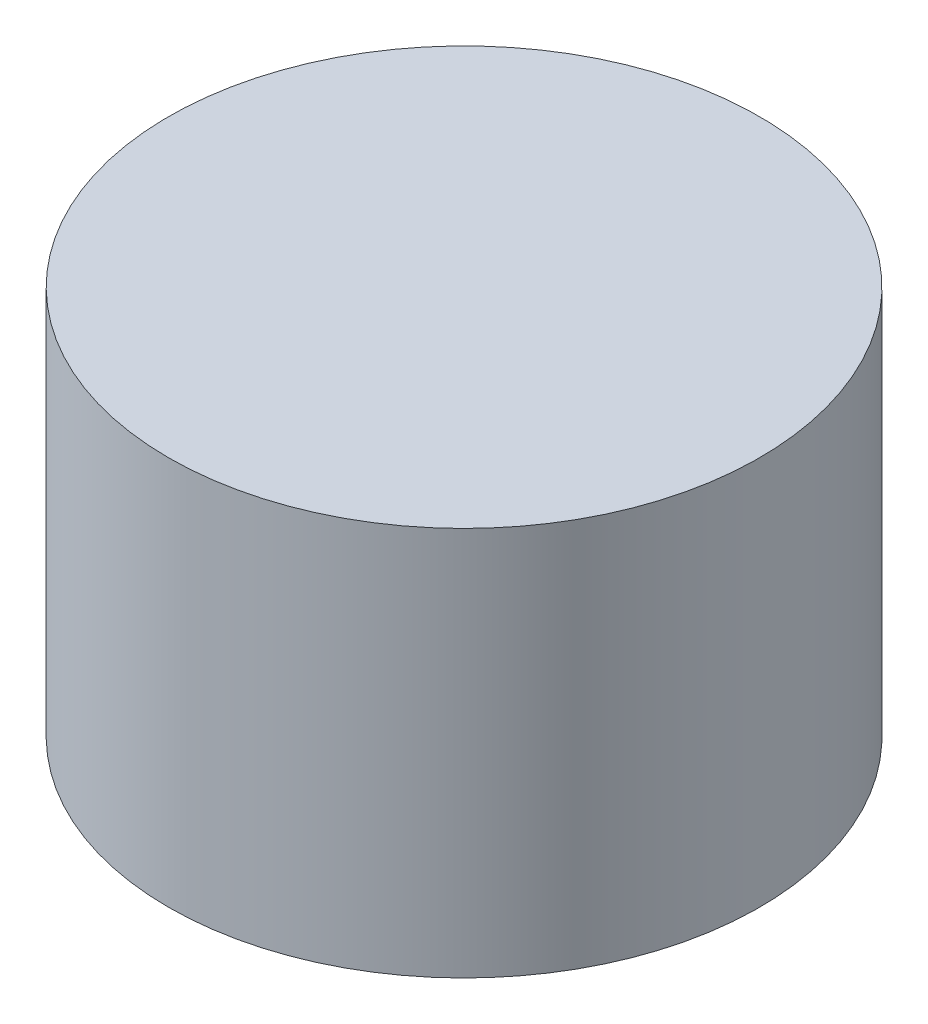
SolidWorks part; units mm, degrees
ref_plane "Front Plane" through (0, 0, 0) normal (0, 0, 1) x (1, 0, 0)
ref_plane "Top Plane" through (0, 0, 0) normal (0, 1, 0) x (1, 0, 0)
ref_plane "Right Plane" through (0, 0, 0) normal (1, 0, 0) x (0, 0, -1)
sketch "Sketch1" plane through (0, 0, 0) normal (0, 1, 0) x (1, 0, 0)
  circle A0 centre (0, 0) radius 38.5562
extrude "Boss-Extrude1" add sketch "Sketch1" along normal blind 50.8
